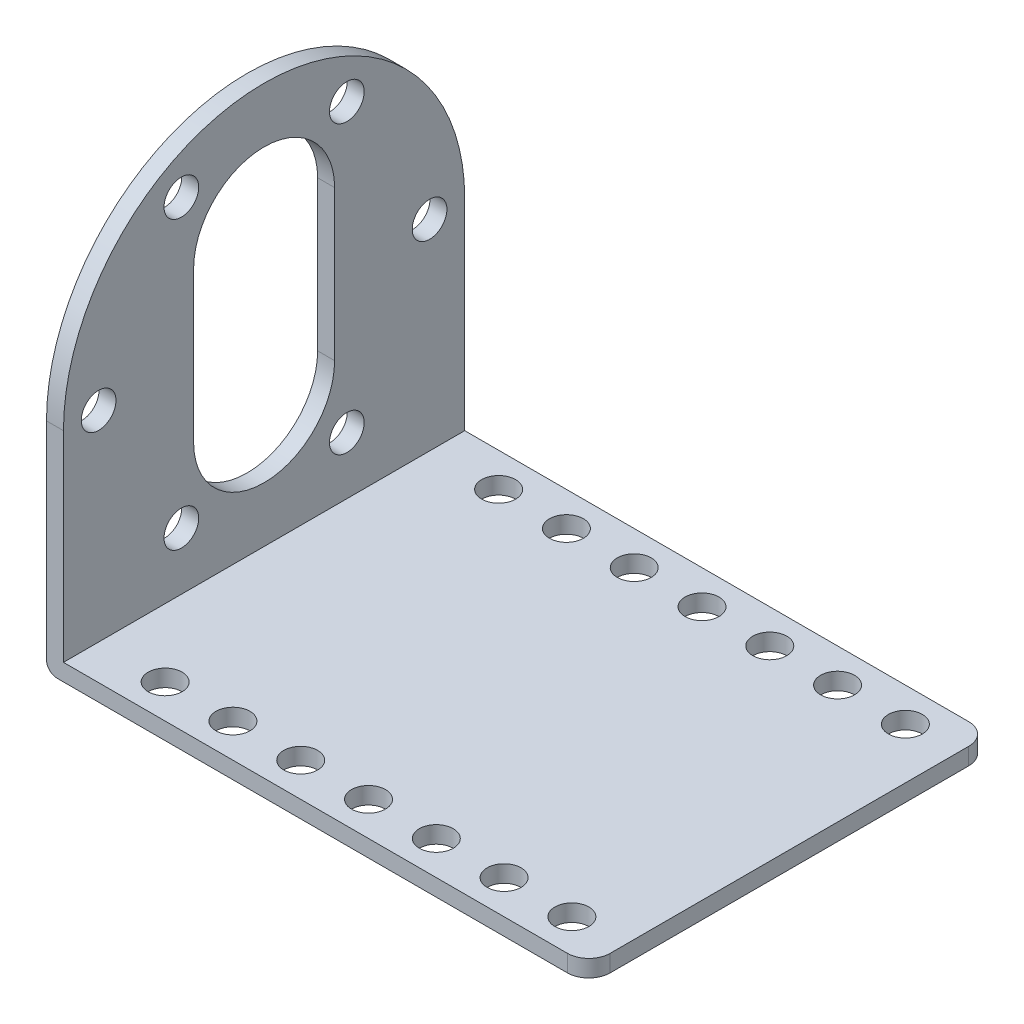
SolidWorks part; units mm, degrees
ref_plane "Plan de face" through (0, 0, 0) normal (0, 0, 1) x (1, 0, 0)
ref_plane "Plan de dessus" through (0, 0, 0) normal (0, 1, 0) x (1, 0, 0)
ref_plane "Plan de droite" through (0, 0, 0) normal (1, 0, 0) x (0, 0, -1)
sketch "Esquisse1" plane through (0, 0, 0) normal (0, 1, 0) x (1, 0, 0)
  line L1 (0, 0) -> (50.8, 0)
  line L2 (0, 0) -> (0, 37.59)
  line L3 (0, 37.59) -> (50.8, 37.59)
  line L4 (50.8, 0) -> (50.8, 37.59)
extrude "Boss.-Extru.1" add sketch "Esquisse1" along normal blind 1.59
sketch "Esquisse2" plane through (0, 1.59, 0) normal (0, 1, 0) x (-1, 0, 0)
  line L0 (0, 0) -> (-50.8, 0) construction
  line L1 (0, -37.59) -> (-1.59, -37.59)
  line L2 (0, -37.59) -> (0, 0)
  line L3 (0, 0) -> (-1.59, 0)
  line L4 (-1.59, -37.59) -> (-1.59, 0)
extrude "Boss.-Extru.2" add sketch "Esquisse2" along normal blind 37.59
fillet "Congé1" radius 1 1 edges at (0, 0, -18.795)
sketch "Esquisse3" plane through (0, 1.59, 0) normal (0, 1, 0) x (1, 0, 0)
  line L0 (50.8, 18.795) -> (1.59, 18.795) construction
  line L1 (50.8, 0) -> (50.8, 37.59) construction
  line L2 (1.59, 0) -> (1.59, 37.59) construction
  line L3 (1.59, 0) -> (1.59, 37.59) construction
  circle A0 centre (7.94, 34.415) radius 1.59
  circle A1 centre (14.29, 34.415) radius 1.59
  circle A2 centre (20.64, 34.415) radius 1.59
  circle A3 centre (26.99, 34.415) radius 1.59
  circle A4 centre (33.34, 34.415) radius 1.59
  circle A5 centre (39.69, 34.415) radius 1.59
  circle A6 centre (46.04, 34.415) radius 1.59
  circle A7 centre (46.04, 3.175) radius 1.59
  circle A8 centre (39.69, 3.175) radius 1.59
  circle A9 centre (33.34, 3.175) radius 1.59
  circle A10 centre (26.99, 3.175) radius 1.59
  circle A11 centre (20.64, 3.175) radius 1.59
  circle A12 centre (14.29, 3.175) radius 1.59
  circle A13 centre (7.94, 3.175) radius 1.59
  dimension "D2" = 6.35
  dimension "D1" = 15.62
  dimension "D3" = 7
extrude "Enlèv. mat.-Extru.1" cut sketch "Esquisse3" against normal through all
fillet "Congé2" radius 2 2 edges at (50.8, 0.795, 0) (50.8, 0.795, -37.59)
sketch "Esquisse4" plane through (1.59, 0, 0) normal (1, 0, 0) x (0, 0, -1)
  line L0 (18.795, 1.59) -> (18.795, 39.18) construction
  line L1 (0, 1.59) -> (37.59, 1.59) construction
  line L2 (0, 39.18) -> (37.59, 39.18) construction
  line L3 (0, 39.18) -> (0, 1.59) construction
  line L4 (37.59, 39.18) -> (37.59, 1.59) construction
  line L5 (0, 20.385) -> (0, 39.18)
  line L6 (0, 39.18) -> (18.795, 39.18)
  line L7 (18.795, 39.18) -> (37.59, 39.18)
  line L8 (37.59, 39.18) -> (37.59, 20.385)
  arc A0 (0, 20.385) -> (37.59, 20.385) centre (18.795, 20.385) cw
  line M2 (37.59, 1.59) -> (37.59, 39.18)
  line M3 (37.59, 39.18) -> (0, 39.18)
  line M4 (0, 39.18) -> (0, 1.59)
extrude "Enlèv. mat.-Extru.2" cut sketch "Esquisse4" against normal through all contours A0 M4 M3 | A0 M3 M2
sketch "Esquisse5" plane through (1.59, 0, 0) normal (1, 0, 0) x (0, 0, -1)
  line L0 (18.795, 1.59) -> (18.795, 39.18) construction
  line L1 (0, 1.59) -> (37.59, 1.59) construction
  line L2 (18.795, 13.365) -> (18.795, 27.405) construction
  line L3 (12.19, 13.365) -> (12.19, 27.405)
  line L4 (25.4, 13.365) -> (25.4, 27.405)
  arc A0 (37.59, 20.385) -> (0, 20.385) centre (18.795, 20.385) ccw construction
  circle A1 centre (18.795, 20.385) radius 15.5 construction
  circle A2 centre (34.295, 20.385) radius 1.625
  circle A3 centre (26.545, 6.9616) radius 1.625
  circle A4 centre (11.045, 6.9616) radius 1.625
  circle A5 centre (3.295, 20.385) radius 1.625
  circle A6 centre (11.045, 33.8084) radius 1.625
  circle A7 centre (26.545, 33.8084) radius 1.625
  arc A8 (12.19, 13.365) -> (25.4, 13.365) centre (18.795, 13.365) ccw
  arc A9 (25.4, 27.405) -> (12.19, 27.405) centre (18.795, 27.405) ccw
  point P13 (18.795, 20.385)
  dimension "D1" = 6
  dimension "D3" = 6.605
  dimension "D2" = 7.02
extrude "Enlèv. mat.-Extru.3" cut sketch "Esquisse5" against normal through all
ref_plane "Plan1" through (0, 0, -18.795) normal (0, 0, 1) x (1, 0, 0)
